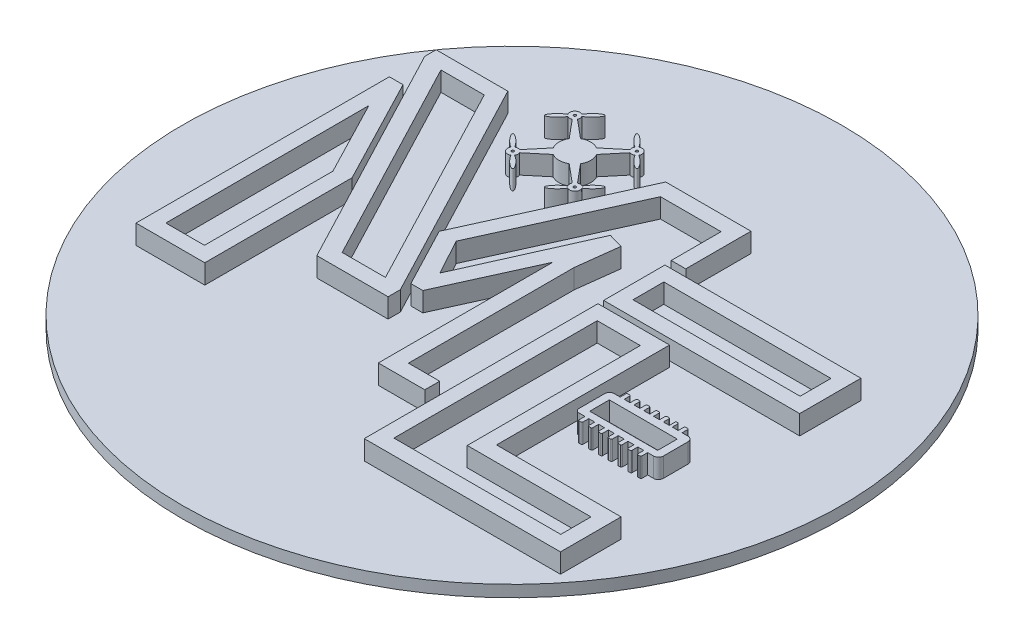
SolidWorks part; units mm, degrees
ref_plane "Plan de face" through (0, 0, 0) normal (0, 0, 1) x (1, 0, 0)
ref_plane "Plan de dessus" through (0, 0, 0) normal (0, 1, 0) x (1, 0, 0)
ref_plane "Plan de droite" through (0, 0, 0) normal (1, 0, 0) x (0, 0, -1)
sketch "Esquisse1" plane through (0, 0, 0) normal (0, 1, 0) x (1, 0, 0)
  line L0 (-107.8494, 0) -> (173.8254, 0) construction
  line L1 (0, -57.2582) -> (0, 177.7302) construction
  line L2 (29.2569, 23.1415) -> (46.9995, 23.1415)
  line L7 (46.9995, 23.1415) -> (46.9995, 61.1356)
  line L8 (46.9995, 61.1356) -> (32.7909, 88.4882)
  line L9 (32.7909, 88.4882) -> (29.2569, 88.4882)
  line L10 (29.2569, 88.4882) -> (29.2569, 23.1415)
  line L11 (33.098, 26.9981) -> (43.0608, 26.9981)
  line L12 (43.0608, 26.9981) -> (43.0608, 60.1213)
  line L13 (43.0608, 60.1213) -> (33.0486, 79.3955)
  line L14 (33.0486, 79.3955) -> (33.098, 26.9981)
  line L15 (78.2274, 39.1905) -> (78.2274, 42.3528)
  line L16 (78.2274, 42.3528) -> (47.7538, 100.5512)
  line L17 (47.7538, 100.5512) -> (29.2569, 100.5512)
  line L18 (29.2569, 100.5512) -> (29.2569, 97.6155)
  line L19 (29.2569, 97.6155) -> (59.8491, 39.1905)
  line L20 (59.8491, 39.1905) -> (78.2274, 39.1905)
  line L21 (62.4047, 43.162) -> (73.5719, 43.162)
  line L22 (73.5719, 43.162) -> (45.5564, 96.6659)
  line L23 (62.4047, 43.162) -> (34.3892, 96.6659)
  line L24 (34.3892, 96.6659) -> (45.5564, 96.6659)
  line L25 (103.7476, 26.9852) -> (103.7476, 23.1415)
  line L26 (103.7476, 23.1415) -> (91.7555, 23.1415)
  line L27 (91.7555, 23.1415) -> (91.7555, 68.1226)
  line L28 (91.7555, 68.1226) -> (81.3169, 45.063)
  line L29 (81.3169, 45.063) -> (78.2274, 45.063)
  line L30 (78.2274, 45.063) -> (70.197, 60.3994)
  line L31 (70.197, 60.3994) -> (88.4076, 100.6276)
  line L32 (88.4076, 100.6276) -> (110.3835, 100.6276)
  line L33 (110.3835, 100.6276) -> (110.3835, 83.8085)
  line L34 (110.3835, 83.8085) -> (106.6388, 83.8085)
  line L35 (106.6388, 83.8085) -> (106.6388, 96.6659)
  line L36 (106.6388, 96.6659) -> (91.0062, 96.6659)
  line L37 (103.7476, 26.9852) -> (95.6873, 26.9852)
  line L38 (95.6873, 26.9852) -> (95.6873, 69.7439)
  line L39 (95.6873, 69.7439) -> (97.0148, 80.4753)
  line L40 (97.0148, 80.4753) -> (93.1813, 81.5745)
  line L41 (93.1813, 81.5745) -> (79.6111, 51.1563)
  line L42 (79.6111, 51.1563) -> (74.5989, 60.3994)
  line L43 (74.5989, 60.3994) -> (91.0062, 96.6659)
  line L44 (69.8, 100.0071) -> (69.8, 81.5745) construction
  line L45 (64.751, 95.7922) -> (74.9536, 95.7922) construction
  line L46 (69.8, 95.7922) -> (59.6693, 85.6615) construction
  line L47 (65.0848, 84.4989) -> (57.6522, 91.9315) construction
  line L48 (110.5469, 60.8128) -> (110.5469, 8.3759)
  line L49 (106.8423, 81.9733) -> (157.403, 81.9733)
  line L50 (106.8423, 81.9733) -> (106.8423, 66.1729)
  line L51 (106.8423, 66.1729) -> (157.403, 66.1729)
  line L52 (157.403, 81.9733) -> (157.403, 66.1729)
  line L53 (110.4828, 78.0601) -> (153.5837, 78.0601)
  line L54 (110.4828, 78.0601) -> (110.4828, 70.1049)
  line L55 (110.4828, 70.1049) -> (153.5837, 70.1049)
  line L56 (153.5837, 78.0601) -> (153.5837, 70.1049)
  line L57 (129.7991, 44.687) -> (147.3076, 44.687)
  line L58 (129.7991, 44.687) -> (129.7991, 39.6316)
  line L59 (129.7991, 39.6316) -> (147.3076, 39.6316)
  line L60 (147.3076, 44.687) -> (147.3076, 39.6316)
  line L61 (110.5469, 8.3759) -> (153.573, 8.3759)
  line L62 (153.573, 8.3759) -> (153.573, 16.1828)
  line L63 (153.573, 16.1828) -> (121.6527, 16.1828)
  line L64 (121.6527, 16.1828) -> (121.6527, 60.8128)
  line L65 (121.6527, 60.8128) -> (110.5469, 60.8128)
  line L66 (106.8423, 64.7105) -> (106.8423, 4.4292)
  line L67 (106.8423, 4.4292) -> (157.4415, 4.4292)
  line L68 (157.4415, 4.4292) -> (157.4415, 20.0723)
  line L69 (157.4415, 20.0723) -> (125.3097, 20.0723)
  line L70 (125.3097, 20.0723) -> (125.3097, 64.7105)
  line L71 (125.3097, 64.7105) -> (106.8423, 64.7105)
  line L72 (130.6109, 48.4102) -> (156.1055, 48.4102) construction
  line L73 (129.5464, 36.11) -> (153.9316, 36.11) construction
  line L74 (128.8067, 46.7221) -> (160.1809, 46.7221) construction
  line L75 (128.5069, 37.8481) -> (153.3982, 37.8481) construction
  line L76 (127.8, 38.8481) -> (127.8, 45.4721)
  line L77 (149.3, 39.0981) -> (149.3, 45.4721)
  line L78 (148.05, 46.7221) -> (146.5187, 46.7221)
  line L79 (146.5187, 46.7221) -> (146.5187, 48.1602)
  line L80 (146.2687, 48.4102) -> (145.7687, 48.4102)
  line L81 (145.5187, 48.1602) -> (145.5187, 46.7221)
  line L82 (145.5187, 46.7221) -> (143.9875, 46.7221)
  line L83 (143.9875, 46.7221) -> (143.9875, 48.1602)
  line L84 (143.7375, 48.4102) -> (143.2375, 48.4102)
  line L85 (143.2375, 48.4102) -> (143.2375, 46.7221)
  line L86 (143.2375, 46.7221) -> (141.7062, 46.7221)
  line L87 (141.7062, 46.7221) -> (141.7062, 48.1602)
  line L88 (141.4562, 48.4102) -> (140.9562, 48.4102)
  line L89 (140.7062, 48.1602) -> (140.7062, 46.7221)
  line L90 (140.7062, 46.7221) -> (139.175, 46.7221)
  line L91 (139.175, 46.7221) -> (139.175, 48.1602)
  line L92 (138.925, 48.4102) -> (138.425, 48.4102)
  line L93 (138.175, 48.1602) -> (138.175, 46.7221)
  line L94 (138.175, 46.7221) -> (136.6438, 46.7221)
  line L95 (136.6438, 46.7221) -> (136.6438, 48.1602)
  line L96 (136.3938, 48.4102) -> (135.8938, 48.4102)
  line L97 (135.6438, 48.1602) -> (135.6438, 46.7221)
  line L98 (135.6438, 46.7221) -> (134.1125, 46.7221)
  line L99 (134.1125, 46.7221) -> (134.1125, 48.1602)
  line L100 (133.8625, 48.4102) -> (133.3625, 48.4102)
  line L101 (133.1125, 48.1602) -> (133.1125, 46.7221)
  line L102 (133.1125, 46.7221) -> (131.5813, 46.7221)
  line L103 (131.5813, 46.7221) -> (131.5813, 48.1602)
  line L104 (131.3313, 48.4102) -> (130.8313, 48.4102)
  line L105 (130.5813, 48.1602) -> (130.5813, 46.7221)
  line L106 (130.5813, 46.7221) -> (129.05, 46.7221)
  line L108 (130.3312, 37.8481) -> (130.3312, 36.36)
  line L109 (130.5812, 36.11) -> (131.0812, 36.11)
  line L110 (131.3313, 36.36) -> (131.3312, 37.8481)
  line L111 (131.3312, 37.8481) -> (132.8625, 37.8481)
  line L112 (132.8625, 37.8481) -> (132.8625, 36.36)
  line L113 (133.1125, 36.11) -> (133.6125, 36.11)
  line L114 (133.8625, 36.36) -> (133.8625, 37.8481)
  line L115 (133.8625, 37.8481) -> (135.3937, 37.8481)
  line L116 (135.3937, 37.8481) -> (135.3937, 36.36)
  line L117 (135.6437, 36.11) -> (136.1437, 36.11)
  line L118 (136.3937, 36.36) -> (136.3937, 37.8481)
  line L119 (136.3937, 37.8481) -> (137.925, 37.8481)
  line L120 (137.925, 37.8481) -> (137.925, 36.36)
  line L121 (138.175, 36.11) -> (138.675, 36.11)
  line L122 (138.925, 36.36) -> (138.925, 37.8481)
  line L123 (138.925, 37.8481) -> (140.4562, 37.8481)
  line L124 (140.4562, 37.8481) -> (140.4562, 36.36)
  line L125 (140.7062, 36.11) -> (141.2062, 36.11)
  line L126 (141.4562, 36.36) -> (141.4562, 37.8481)
  line L127 (141.4562, 37.8481) -> (142.9875, 37.8481)
  line L128 (142.9875, 37.8481) -> (142.9875, 36.36)
  line L129 (143.2375, 36.11) -> (143.7375, 36.11)
  line L130 (143.9875, 36.36) -> (143.9875, 37.8481)
  line L131 (143.9875, 37.8481) -> (145.5187, 37.8481)
  line L132 (145.5187, 37.8481) -> (145.5187, 36.36)
  line L133 (145.7687, 36.11) -> (146.2687, 36.11)
  line L134 (146.5187, 36.36) -> (146.5187, 37.8481)
  line L135 (146.5187, 37.8481) -> (148.05, 37.8481)
  line L136 (66.8959, 94.4746) -> (61.794, 88.3632) construction
  line L137 (62.3325, 89.0083) -> (66.2713, 93.7264)
  line L138 (63.0161, 88.3247) -> (67.7342, 92.2635)
  line L139 (62.3325, 102.5761) -> (66.2713, 97.858)
  line L140 (63.0161, 103.2597) -> (67.7342, 99.3209)
  line L141 (76.5839, 103.2597) -> (71.8658, 99.3209)
  line L142 (77.2675, 102.5761) -> (73.3287, 97.858)
  line L143 (77.2675, 89.0083) -> (73.3287, 93.7264)
  line L144 (76.5839, 88.3247) -> (71.8658, 92.2635)
  line L145 (128.8, 37.8481) -> (130.3312, 37.8481)
  line L146 (157.403, 85.1296) -> (157.403, -9.43) construction
  line L147 (153.5837, 85.1296) -> (153.5837, -16.5229) construction
  arc A0 (65.7111, 95.7922) -> (66.2713, 93.7264) centre (69.8, 95.7922) ccw
  arc A1 (62.3325, 89.0083) -> (61.118, 88.936) centre (61.7958, 87.788) ccw
  arc A2 (60.6475, 88.4658) -> (62.4736, 86.6397) centre (61.7958, 87.788) ccw
  arc A3 (69.8, 91.7033) -> (67.7342, 92.2635) centre (69.8, 95.7922) cw
  arc A4 (63.0161, 88.3247) -> (62.9438, 87.1102) centre (61.7958, 87.788) cw
  circle A5 centre (61.7958, 87.788) radius 0.3155
  arc A6 (62.4736, 104.9447) -> (60.6475, 103.1186) centre (61.7958, 103.7964) ccw
  arc A7 (62.3325, 102.5761) -> (61.118, 102.6484) centre (61.7958, 103.7964) cw
  arc A8 (63.0161, 103.2597) -> (62.9438, 104.4742) centre (61.7958, 103.7964) ccw
  circle A9 centre (61.7958, 103.7964) radius 0.3155
  arc A10 (65.7111, 95.7922) -> (66.2713, 97.858) centre (69.8, 95.7922) cw
  arc A11 (69.8, 99.8811) -> (67.7342, 99.3209) centre (69.8, 95.7922) ccw
  arc A12 (78.9525, 103.1186) -> (77.1264, 104.9447) centre (77.8042, 103.7964) ccw
  arc A13 (76.5839, 103.2597) -> (76.6562, 104.4742) centre (77.8042, 103.7964) cw
  arc A14 (77.2675, 102.5761) -> (78.482, 102.6484) centre (77.8042, 103.7964) ccw
  circle A15 centre (77.8042, 103.7964) radius 0.3155
  arc A16 (69.8, 99.8811) -> (71.8658, 99.3209) centre (69.8, 95.7922) cw
  arc A17 (73.8889, 95.7922) -> (73.3287, 97.858) centre (69.8, 95.7922) ccw
  arc A18 (77.1264, 86.6397) -> (78.9525, 88.4658) centre (77.8042, 87.788) ccw
  arc A19 (77.2675, 89.0083) -> (78.482, 88.936) centre (77.8042, 87.788) cw
  arc A20 (76.5839, 88.3247) -> (76.6562, 87.1102) centre (77.8042, 87.788) ccw
  circle A21 centre (77.8042, 87.788) radius 0.3155
  arc A22 (73.8889, 95.7922) -> (73.3287, 93.7264) centre (69.8, 95.7922) cw
  arc A23 (69.8, 91.7033) -> (71.8658, 92.2635) centre (69.8, 95.7922) ccw
  arc A25 (127.8, 45.4721) -> (129.05, 46.7221) centre (129.05, 45.4721) cw
  arc A26 (149.3, 45.4721) -> (148.05, 46.7221) centre (148.05, 45.4721) ccw
  arc A27 (149.3, 39.0981) -> (148.05, 37.8481) centre (148.05, 39.0981) cw
  arc A28 (146.2687, 36.11) -> (146.5187, 36.36) centre (146.2687, 36.36) ccw
  arc A29 (145.5187, 36.36) -> (145.7687, 36.11) centre (145.7687, 36.36) ccw
  arc A30 (143.7375, 36.11) -> (143.9875, 36.36) centre (143.7375, 36.36) ccw
  arc A31 (142.9875, 36.36) -> (143.2375, 36.11) centre (143.2375, 36.36) ccw
  arc A32 (141.2062, 36.11) -> (141.4562, 36.36) centre (141.2062, 36.36) ccw
  arc A33 (140.4562, 36.36) -> (140.7062, 36.11) centre (140.7062, 36.36) ccw
  arc A34 (138.675, 36.11) -> (138.925, 36.36) centre (138.675, 36.36) ccw
  arc A35 (137.925, 36.36) -> (138.175, 36.11) centre (138.175, 36.36) ccw
  arc A36 (136.1437, 36.11) -> (136.3937, 36.36) centre (136.1437, 36.36) ccw
  arc A37 (135.3937, 36.36) -> (135.6437, 36.11) centre (135.6437, 36.36) ccw
  arc A38 (133.6125, 36.11) -> (133.8625, 36.36) centre (133.6125, 36.36) ccw
  arc A39 (132.8625, 36.36) -> (133.1125, 36.11) centre (133.1125, 36.36) ccw
  arc A40 (131.0812, 36.11) -> (131.3313, 36.36) centre (131.0812, 36.36) ccw
  arc A41 (130.3312, 36.36) -> (130.5812, 36.11) centre (130.5812, 36.36) ccw
  arc A42 (146.5187, 48.1602) -> (146.2687, 48.4102) centre (146.2687, 48.1602) ccw
  arc A43 (145.7687, 48.4102) -> (145.5187, 48.1602) centre (145.7687, 48.1602) ccw
  arc A44 (143.9875, 48.1602) -> (143.7375, 48.4102) centre (143.7375, 48.1602) ccw
  arc A45 (141.7062, 48.1602) -> (141.4562, 48.4102) centre (141.4562, 48.1602) ccw
  arc A46 (140.9562, 48.4102) -> (140.7062, 48.1602) centre (140.9562, 48.1602) ccw
  arc A47 (139.175, 48.1602) -> (138.925, 48.4102) centre (138.925, 48.1602) ccw
  arc A48 (138.425, 48.4102) -> (138.175, 48.1602) centre (138.425, 48.1602) ccw
  arc A49 (136.6438, 48.1602) -> (136.3938, 48.4102) centre (136.3938, 48.1602) ccw
  arc A50 (135.8938, 48.4102) -> (135.6438, 48.1602) centre (135.8938, 48.1602) ccw
  arc A51 (134.1125, 48.1602) -> (133.8625, 48.4102) centre (133.8625, 48.1602) ccw
  arc A52 (133.3625, 48.4102) -> (133.1125, 48.1602) centre (133.3625, 48.1602) ccw
  arc A53 (131.5813, 48.1602) -> (131.3313, 48.4102) centre (131.3313, 48.1602) ccw
  arc A54 (130.8313, 48.4102) -> (130.5813, 48.1602) centre (130.8313, 48.1602) ccw
  arc A55 (127.8, 38.8481) -> (128.8, 37.8481) centre (128.8, 38.8481) ccw
  ellipse E0 centre (59.5392, 90.0446) end of major axis (57.882, 91.7017) minor radius 0.5682
  ellipse E1 centre (64.0524, 85.5314) end of major axis (65.7095, 83.8742) minor radius 0.5682
  ellipse E2 centre (64.0524, 106.053) end of major axis (62.3952, 104.3959) minor radius 0.5682
  ellipse E3 centre (59.5392, 101.5398) end of major axis (61.1963, 103.197) minor radius 0.5682
  ellipse E4 centre (80.0608, 101.5398) end of major axis (81.718, 99.8827) minor radius 0.5682
  ellipse E5 centre (75.5476, 106.053) end of major axis (73.8905, 107.7102) minor radius 0.5682
  ellipse E6 centre (75.5476, 85.5314) end of major axis (73.8905, 83.8742) minor radius 0.5682
  ellipse E7 centre (80.0608, 90.0446) end of major axis (81.718, 91.7017) minor radius 0.5682
  point P245 (69.8, 95.7922)
  point P248 (149.3, 46.7221)
  point P251 (149.3, 37.8481)
  point P254 (146.5187, 36.11)
  point P257 (145.5187, 36.11)
  point P260 (143.9875, 36.11)
  point P263 (142.9875, 36.11)
  point P266 (141.4562, 36.11)
  point P269 (140.4562, 36.11)
  point P272 (138.925, 36.11)
  point P275 (137.925, 36.11)
  point P278 (136.3937, 36.11)
  point P281 (135.3937, 36.11)
  point P284 (133.8625, 36.11)
  point P287 (132.8625, 36.11)
  point P290 (131.3312, 36.11)
  point P293 (130.3312, 36.11)
  point P296 (146.5187, 48.4102)
  point P299 (145.5187, 48.4102)
  point P302 (143.9875, 48.4102)
  point P305 (141.7062, 48.4102)
  point P308 (140.7062, 48.4102)
  point P311 (139.175, 48.4102)
  point P314 (138.175, 48.4102)
  point P317 (136.6438, 48.4102)
  point P320 (135.6438, 48.4102)
  point P323 (134.1125, 48.4102)
  point P326 (133.1125, 48.4102)
  point P329 (131.5813, 48.4102)
  point P332 (130.5813, 48.4102)
  dimension "D7" = 90
  dimension "D8" = 4
  dimension "D10" = 1
  dimension "D11" = 0.25
  dimension "D3" = 1
  dimension "D5" = 21.5
  dimension "D6" = 1.6881
  dimension "D9" = 69.8
  dimension "D12" = 127.8
  dimension "D13" = 46.7221
extrude "Boss.-Extru.1" add sketch "Esquisse1" along normal blind 5 contours L19 L20 L15 L16 L17 L18 L23 L24 L22 L21 | L9 L10 L2 L7 L8 L14 L13 L12 L11 | A18 E7 A19 L143 A22 A17 L142 A14 E4 A12 E5 A13 L141 A16 A11 L140 A8 E2 A6 E3 A7 L139 A10 A0 L137 A1 E0 A2 E1 A4 L138 A3 A23 L144 A20 E6 A21 A15 A9 A5 | E6 | E7 | E4 | E5 | E3 | E0 | E1 | E2 | L42 L43 L36 L35 L34 L33 L32 L31 L30 L29 L28 L27 L26 L25 L37 L38 L39 L40 L41 | L52 L49 L50 L51 L53 L56 L55 L54 | L76 A55 L145 L108 A41 L109 A40 L110 L111 L112 A39 L113 A38 L114 L115 L116 A37 L117 A36 L118 L119 L120 A35 L121 A34 L122 L123 L124 A33 L125 A32 L126 L127 L128 A31 L129 A30 L130 L131 L132 A29 L133 A28 L134 L135 A27 L77 A26 L78 L79 A42 | L70 L71 L66 L67 L68 L69 L65 L64 L63 L62 L61 L48
sketch "Esquisse3" plane through (0, 0, 0) normal (0, -1, 0) x (1, 0, 0)
  line L0 (106.8423, -4.4292) -> (157.4415, -4.4292) construction
  line L1 (29.2569, -88.4882) -> (29.2569, -23.1415) construction
  line L3 (29.2569, -88.4882) -> (29.2569, -23.1415)
  line L4 (29.2569, 4.6266) -> (29.2569, -123.0203) construction
  line L5 (23.2722, -4.4292) -> (190.8601, -4.4292) construction
  line L6 (65.7517, -107.6283) -> (24.0642, -107.6283) construction
  line L7 (93.3492, -4.4292) -> (93.3492, -107.6283) construction
  line L12 (29.2569, -55.8149) -> (157.4415, -56.0287) construction
  circle A0 centre (93.3492, -56.0287) radius 85
  ellipse E0 centre (64.0524, -106.053) end of major axis (65.7095, -107.7102) minor radius 0.5682 (62.4736, -104.9447) -> (62.9438, -104.4742) ccw construction
  dimension "D1" = 170
extrude "Boss.-Extru.2" add sketch "Esquisse3" along normal blind 3
sketch "Esquisse4" plane through (0, 0, 0) normal (0, 1, 0) x (1, 0, 0)
  circle A2 centre (93.3492, 56.0287) radius 85
  circle A3 centre (93.3492, 56.0287) radius 85
  dimension "D1" = 0
